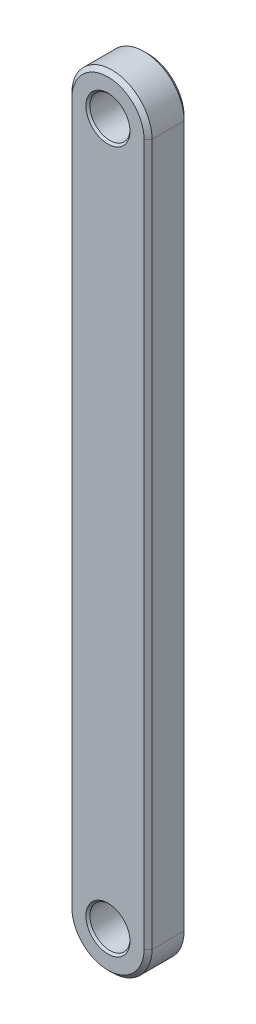
SolidWorks part; units mm, degrees
ref_plane "Front Plane" through (0, 0, 0) normal (0, 0, 1) x (1, 0, 0)
ref_plane "Top Plane" through (0, 0, 0) normal (0, 1, 0) x (1, 0, 0)
ref_plane "Right Plane" through (0, 0, 0) normal (1, 0, 0) x (0, 0, -1)
sketch "Sketch1" plane through (0, 0, 0) normal (0, 0, 1) x (1, 0, 0)
  line L0 (0, -17.5) -> (0, 17.5) construction
  line L1 (-2, -17.5) -> (-2, 17.5)
  line L2 (2, -17.5) -> (2, 17.5)
  arc A0 (-2, -17.5) -> (2, -17.5) centre (0, -17.5) ccw
  arc A1 (2, 17.5) -> (-2, 17.5) centre (0, 17.5) ccw
  circle A2 centre (0, 17.5) radius 1
  circle A3 centre (0, -17.5) radius 1
  point P2 (0, 0)
  point P10 (0, 0)
  point P13 (0, 0)
  dimension "D2" = 2
  dimension "D3" = 2
  dimension "D1" = 35
extrude "Boss-Extrude1" add sketch "Sketch1" along normal mid plane 2
chamfer "Chamfer1" distance 0.2 angle 45 8 edges at (-2, 0, -1) (0, -19.5, -1) (0, 19.5, -1) (2, 0, -1) (-2, 0, 1) (0, -19.5, 1) (0, 19.5, 1) (2, 0, 1)
chamfer "Chamfer2" distance 0.1 angle 45 4 edges at (1, -17.5, 1) (1, -17.5, -1) (1, 17.5, -1) (1, 17.5, 1)
